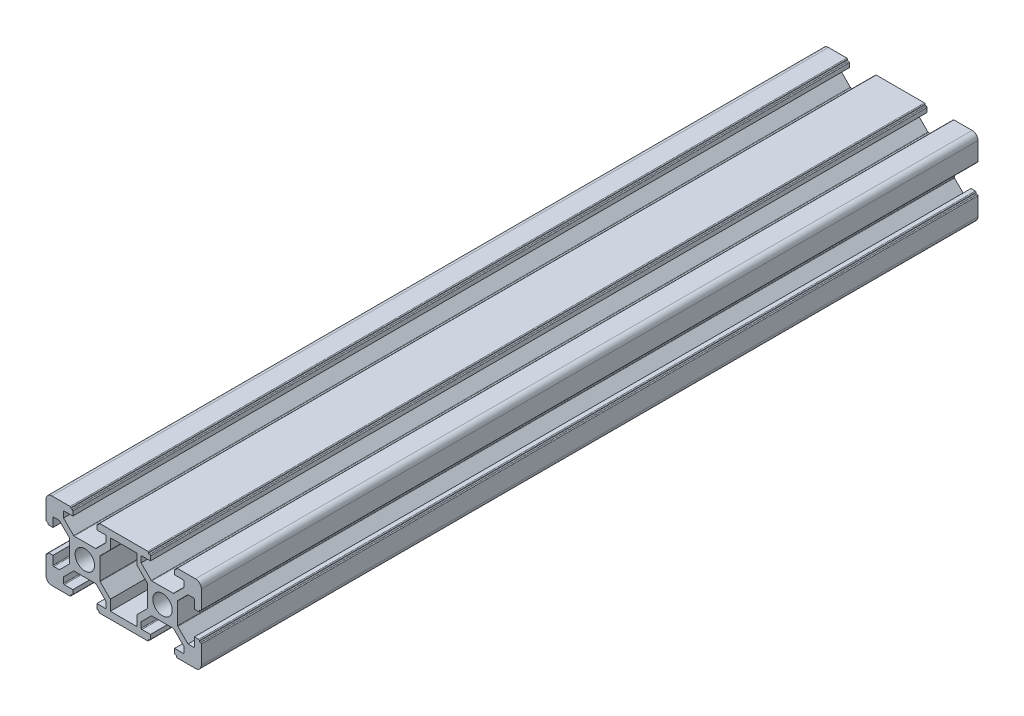
SolidWorks part; units mm, degrees
ref_plane "前视基准面" through (0, 0, 0) normal (0, 0, 1) x (1, 0, 0)
ref_plane "上视基准面" through (0, 0, 0) normal (0, 1, 0) x (1, 0, 0)
ref_plane "右视基准面" through (0, 0, 0) normal (1, 0, 0) x (0, 0, -1)
sketch "Sketch1" plane through (0, 0, 0) normal (0, 0, 1) x (1, 0, 0)
  line L0 (-8.5, 10) -> (-3.8, 10)
  line L3 (-8.5, -10) -> (-3.8, -10)
  line L5 (-10, 8.5) -> (-10, 3.8)
  line L6 (-2.7565, 3.9) -> (2.7565, 3.9)
  line L9 (-2.7565, -3.9) -> (2.7565, -3.9)
  line L10 (3.9, 2.7565) -> (3.9, -2.7565)
  line L11 (-3.9, 2.7565) -> (-3.9, -2.7565)
  line L12 (-3.9586, -2.8979) -> (-6.5607, -5.5)
  line L13 (3.6, 9.7) -> (3.6, 9.8)
  line L14 (3.1, -8.2) -> (5.3, -8.2)
  line L15 (-2.8979, -3.9586) -> (-5.5, -6.5607)
  line L16 (-3.1, -8.2) -> (-3.1, -9.3)
  line L17 (3.1, -8.2) -> (3.1, -9.3)
  line L18 (-5.5, -6.5607) -> (-5.5, -8)
  line L19 (5.5, -6.5607) -> (5.5, -8)
  line L20 (-5.3, -8.2) -> (-3.1, -8.2)
  line L21 (-3.4, -9.5) -> (-3.3, -9.5)
  line L22 (3.8, -10) -> (8.5, -10)
  line L23 (3.3, -9.5) -> (3.4, -9.5)
  line L24 (-3.6, -9.7) -> (-3.6, -9.8)
  line L25 (3.6, -9.7) -> (3.6, -9.8)
  line L26 (-6.5607, -5.5) -> (-8, -5.5)
  line L27 (-9.7, -3.6) -> (-9.8, -3.6)
  line L28 (-9.5, -3.4) -> (-9.5, -3.3)
  line L29 (-8.2, -3.1) -> (-9.3, -3.1)
  line L30 (-8.2, -5.3) -> (-8.2, -3.1)
  line L31 (-10, -3.8) -> (-10, -8.5)
  line L33 (3.8, 10) -> (8.5, 10)
  line L34 (2.8979, -3.9586) -> (5.5, -6.5607)
  line L40 (3.9586, -2.8979) -> (6.5607, -5.5)
  line L41 (3.3, 9.5) -> (3.4, 9.5)
  line L42 (30, 8.5) -> (30, 3.8)
  line L43 (3.1, 8.2) -> (3.1, 9.3)
  line L44 (3.1, 8.2) -> (5.3, 8.2)
  line L45 (5.5, 6.5607) -> (5.5, 8)
  line L46 (2.8979, 3.9586) -> (5.5, 6.5607)
  line L52 (3.9586, 2.8979) -> (6.5607, 5.5)
  line L53 (-3.6, 9.7) -> (-3.6, 9.8)
  line L54 (-3.4, 9.5) -> (-3.3, 9.5)
  line L55 (-3.1, 8.2) -> (-3.1, 9.3)
  line L56 (-5.3, 8.2) -> (-3.1, 8.2)
  line L57 (-5.5, 6.5607) -> (-5.5, 8)
  line L58 (-2.8979, 3.9586) -> (-5.5, 6.5607)
  line L59 (-9.5, 3.4) -> (-9.5, 3.3)
  line L60 (-9.7, 3.6) -> (-9.8, 3.6)
  line L61 (-8.2, 3.1) -> (-9.3, 3.1)
  line L62 (-8.2, 5.3) -> (-8.2, 3.1)
  line L63 (-6.5607, 5.5) -> (-8, 5.5)
  line L64 (-3.9586, 2.8979) -> (-6.5607, 5.5)
  line L65 (29.7, 3.6) -> (29.8, 3.6)
  line L66 (29.5, 3.4) -> (29.5, 3.3)
  line L67 (28.2, 3.1) -> (29.3, 3.1)
  line L68 (28.2, 5.3) -> (28.2, 3.1)
  line L69 (26.5607, 5.5) -> (28, 5.5)
  line L70 (23.9586, 2.8979) -> (26.5607, 5.5)
  line L71 (23.9, 2.7565) -> (23.9, -2.7565)
  line L72 (23.9586, -2.8979) -> (26.5607, -5.5)
  line L73 (26.5607, -5.5) -> (28, -5.5)
  line L74 (28.2, -5.3) -> (28.2, -3.1)
  line L75 (28.2, -3.1) -> (29.3, -3.1)
  line L76 (29.5, -3.4) -> (29.5, -3.3)
  line L77 (29.7, -3.6) -> (29.8, -3.6)
  line L78 (30, -3.8) -> (30, -8.5)
  line L79 (28.5, -10) -> (23.8, -10)
  line L80 (23.6, -9.7) -> (23.6, -9.8)
  line L81 (23.4, -9.5) -> (23.3, -9.5)
  line L82 (23.1, -8.2) -> (23.1, -9.3)
  line L83 (25.3, -8.2) -> (23.1, -8.2)
  line L84 (25.5, -6.5607) -> (25.5, -8)
  line L85 (22.8979, -3.9586) -> (25.5, -6.5607)
  line L86 (22.7565, -3.9) -> (17.2435, -3.9)
  line L87 (17.1021, -3.9586) -> (14.5, -6.5607)
  line L88 (14.5, -6.5607) -> (14.5, -8)
  line L89 (16.9, -8.2) -> (14.7, -8.2)
  line L90 (16.9, -8.2) -> (16.9, -9.3)
  line L91 (16.7, -9.5) -> (16.6, -9.5)
  line L92 (16.4, -9.7) -> (16.4, -9.8)
  line L93 (16.2, -10) -> (11.5, -10)
  line L94 (13.4393, 5.5) -> (13.4393, 8.2)
  line L96 (6.5607, 5.5) -> (6.5607, 8.2)
  line L97 (6.5607, 8.2) -> (13.4393, 8.2)
  line L99 (16.0414, -2.8979) -> (13.4393, -5.5)
  line L100 (16.1, 2.7565) -> (16.1, -2.7565)
  line L101 (16.0414, 2.8979) -> (13.4393, 5.5)
  line L107 (16.2, 10) -> (11.5, 10)
  line L108 (16.4, 9.7) -> (16.4, 9.8)
  line L109 (16.7, 9.5) -> (16.6, 9.5)
  line L110 (16.9, 8.2) -> (16.9, 9.3)
  line L111 (16.9, 8.2) -> (14.7, 8.2)
  line L112 (14.5, 6.5607) -> (14.5, 8)
  line L113 (17.1021, 3.9586) -> (14.5, 6.5607)
  line L114 (22.7565, 3.9) -> (17.2435, 3.9)
  line L115 (22.8979, 3.9586) -> (25.5, 6.5607)
  line L116 (25.5, 6.5607) -> (25.5, 8)
  line L117 (25.3, 8.2) -> (23.1, 8.2)
  line L118 (23.1, 8.2) -> (23.1, 9.3)
  line L119 (23.4, 9.5) -> (23.3, 9.5)
  line L120 (23.6, 9.7) -> (23.6, 9.8)
  line L121 (28.5, 10) -> (23.8, 10)
  line L122 (13.4393, -5.5) -> (13.4393, -8.2)
  line L124 (6.5607, -5.5) -> (6.5607, -8.2)
  line L125 (6.5607, -8.2) -> (13.4393, -8.2)
  line L127 (8.5, 10) -> (11.5, 10)
  line L128 (8.5, -10) -> (11.5, -10)
  arc A3 (-8.5, -10) -> (-10, -8.5) centre (-8.5, -8.5) cw
  arc A4 (-10, 8.5) -> (-8.5, 10) centre (-8.5, 8.5) cw
  arc A5 (3.4, -9.5) -> (3.6, -9.7) centre (3.4, -9.7) cw
  arc A6 (3.8, -10) -> (3.6, -9.8) centre (3.8, -9.8) cw
  arc A7 (3.3, -9.5) -> (3.1, -9.3) centre (3.3, -9.3) cw
  arc A8 (5.3, -8.2) -> (5.5, -8) centre (5.3, -8) ccw
  arc A9 (-3.9, -2.7565) -> (-3.9586, -2.8979) centre (-4.1, -2.7565) cw
  arc A10 (-3.9, 2.7565) -> (-3.9586, 2.8979) centre (-4.1, 2.7565) ccw
  arc A11 (-2.7565, 3.9) -> (-2.8979, 3.9586) centre (-2.7565, 4.1) cw
  arc A12 (2.7565, 3.9) -> (2.8979, 3.9586) centre (2.7565, 4.1) ccw
  arc A13 (3.9586, 2.8979) -> (3.9, 2.7565) centre (4.1, 2.7565) ccw
  arc A14 (3.9, -2.7565) -> (3.9586, -2.8979) centre (4.1, -2.7565) ccw
  arc A15 (-2.8979, -3.9586) -> (-2.7565, -3.9) centre (-2.7565, -4.1) cw
  arc A16 (2.7565, -3.9) -> (2.8979, -3.9586) centre (2.7565, -4.1) cw
  arc A17 (-3.6, -9.8) -> (-3.8, -10) centre (-3.8, -9.8) cw
  arc A18 (-3.3, -9.5) -> (-3.1, -9.3) centre (-3.3, -9.3) ccw
  arc A19 (-3.6, -9.7) -> (-3.4, -9.5) centre (-3.4, -9.7) cw
  arc A20 (-8.2, 5.3) -> (-8, 5.5) centre (-8, 5.3) cw
  arc A23 (-8.2, -5.3) -> (-8, -5.5) centre (-8, -5.3) ccw
  arc A24 (-5.3, -8.2) -> (-5.5, -8) centre (-5.3, -8) cw
  arc A31 (3.1, 9.3) -> (3.3, 9.5) centre (3.3, 9.3) cw
  arc A32 (3.6, 9.8) -> (3.8, 10) centre (3.8, 9.8) cw
  arc A33 (3.6, 9.7) -> (3.4, 9.5) centre (3.4, 9.7) cw
  arc A34 (-3.8, 10) -> (-3.6, 9.8) centre (-3.8, 9.8) cw
  arc A35 (-3.3, 9.5) -> (-3.1, 9.3) centre (-3.3, 9.3) cw
  arc A36 (-3.4, 9.5) -> (-3.6, 9.7) centre (-3.4, 9.7) cw
  arc A37 (5.5, 8) -> (5.3, 8.2) centre (5.3, 8) ccw
  arc A38 (-5.5, 8) -> (-5.3, 8.2) centre (-5.3, 8) cw
  arc A39 (-10, 3.8) -> (-9.8, 3.6) centre (-9.8, 3.8) ccw
  arc A40 (-9.5, 3.3) -> (-9.3, 3.1) centre (-9.3, 3.3) ccw
  arc A41 (-9.7, 3.6) -> (-9.5, 3.4) centre (-9.7, 3.4) cw
  arc A42 (-10, -3.8) -> (-9.8, -3.6) centre (-9.8, -3.8) cw
  arc A43 (-9.5, -3.3) -> (-9.3, -3.1) centre (-9.3, -3.3) cw
  arc A44 (-9.5, -3.4) -> (-9.7, -3.6) centre (-9.7, -3.4) cw
  arc A45 (30, 8.5) -> (28.5, 10) centre (28.5, 8.5) ccw
  arc A46 (30, 3.8) -> (29.8, 3.6) centre (29.8, 3.8) cw
  arc A47 (29.7, 3.6) -> (29.5, 3.4) centre (29.7, 3.4) ccw
  arc A48 (29.5, 3.3) -> (29.3, 3.1) centre (29.3, 3.3) cw
  arc A49 (28.2, 5.3) -> (28, 5.5) centre (28, 5.3) ccw
  arc A50 (23.9, 2.7565) -> (23.9586, 2.8979) centre (24.1, 2.7565) cw
  arc A51 (23.9, -2.7565) -> (23.9586, -2.8979) centre (24.1, -2.7565) ccw
  arc A52 (28.2, -5.3) -> (28, -5.5) centre (28, -5.3) cw
  arc A53 (29.5, -3.3) -> (29.3, -3.1) centre (29.3, -3.3) ccw
  arc A54 (29.5, -3.4) -> (29.7, -3.6) centre (29.7, -3.4) ccw
  arc A55 (30, -3.8) -> (29.8, -3.6) centre (29.8, -3.8) ccw
  arc A56 (28.5, -10) -> (30, -8.5) centre (28.5, -8.5) ccw
  arc A57 (23.6, -9.8) -> (23.8, -10) centre (23.8, -9.8) ccw
  arc A58 (23.6, -9.7) -> (23.4, -9.5) centre (23.4, -9.7) ccw
  arc A59 (23.3, -9.5) -> (23.1, -9.3) centre (23.3, -9.3) cw
  arc A60 (25.3, -8.2) -> (25.5, -8) centre (25.3, -8) ccw
  arc A61 (22.8979, -3.9586) -> (22.7565, -3.9) centre (22.7565, -4.1) ccw
  arc A62 (17.2435, -3.9) -> (17.1021, -3.9586) centre (17.2435, -4.1) ccw
  arc A63 (14.7, -8.2) -> (14.5, -8) centre (14.7, -8) cw
  arc A64 (16.7, -9.5) -> (16.9, -9.3) centre (16.7, -9.3) ccw
  arc A65 (16.6, -9.5) -> (16.4, -9.7) centre (16.6, -9.7) ccw
  arc A66 (16.2, -10) -> (16.4, -9.8) centre (16.2, -9.8) ccw
  arc A72 (16.1, -2.7565) -> (16.0414, -2.8979) centre (15.9, -2.7565) cw
  arc A73 (16.0414, 2.8979) -> (16.1, 2.7565) centre (15.9, 2.7565) cw
  arc A79 (16.4, 9.8) -> (16.2, 10) centre (16.2, 9.8) ccw
  arc A80 (16.4, 9.7) -> (16.6, 9.5) centre (16.6, 9.7) ccw
  arc A81 (16.9, 9.3) -> (16.7, 9.5) centre (16.7, 9.3) ccw
  arc A82 (14.5, 8) -> (14.7, 8.2) centre (14.7, 8) cw
  arc A83 (17.2435, 3.9) -> (17.1021, 3.9586) centre (17.2435, 4.1) cw
  arc A84 (22.7565, 3.9) -> (22.8979, 3.9586) centre (22.7565, 4.1) ccw
  arc A85 (25.5, 8) -> (25.3, 8.2) centre (25.3, 8) ccw
  arc A86 (23.3, 9.5) -> (23.1, 9.3) centre (23.3, 9.3) ccw
  arc A87 (23.4, 9.5) -> (23.6, 9.7) centre (23.4, 9.7) ccw
  arc A88 (23.8, 10) -> (23.6, 9.8) centre (23.8, 9.8) ccw
  point P11 (3.9, 3.9)
  point P19 (3.3697, 4.4303)
  point P20 (-10.6428, -10.6428)
  point P25 (-11.1731, -10.1124)
  point P26 (4.4303, 3.3697)
  point P28 (-10.1124, -11.1731)
  dimension "D3" = 0.2
  dimension "D4" = 0.2
  dimension "D5" = 0.2
  dimension "D8" = 0.2
  dimension "D9" = 0.2
  dimension "D10" = 0.2
  dimension "D6" = 1.8
  dimension "D7" = 0.5
extrude "Boss-Extrude1" add sketch "Sketch1" along normal blind 200
ref_plane "hole" through (0, 0, 200) normal (0, 0, 1) x (1, 0, 0)
sketch "Sketch2" plane through (0, 0, 200) normal (0, 0, 1) x (1, 0, 0)
  circle A0 centre (0, 0) radius 2.5
  circle A1 centre (20, 0) radius 2.5
  dimension "D1" = 5
extrude "Cut-Extrude1" cut sketch "Sketch2" against normal through all
sketch "Sketch3" plane through (23.9, 0, 0) normal (1, 0, 0) x (0, 0, -1)
  line L0 (-200, -2.7565) -> (-200, 2.7565) construction
  circle A0 centre (-183.3, 0) radius 1.5
  circle A1 centre (-166.6, 0) radius 1.5
  point P6 (-200, 0)
  dimension "D1" = 3
  dimension "D2" = 16.7
  dimension "D3" = 0
  dimension "D4" = 0
  dimension "D5" = 3
  dimension "D6" = 16.7
extrude "Cut-Extrude2" cut sketch "Sketch3" against normal blind 65
